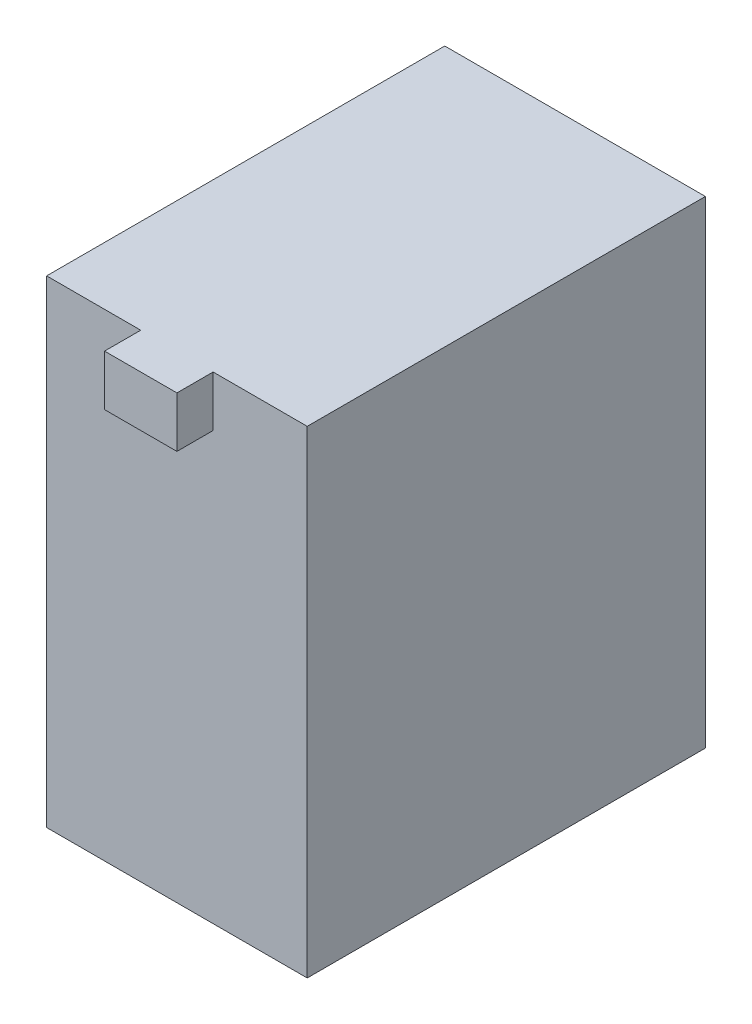
SolidWorks part; units mm, degrees
ref_plane "前视基准面" through (0, 0, 0) normal (0, 0, 1) x (1, 0, 0)
ref_plane "上视基准面" through (0, 0, 0) normal (0, 1, 0) x (1, 0, 0)
ref_plane "右视基准面" through (0, 0, 0) normal (1, 0, 0) x (0, 0, -1)
other "Configuration Table"
sketch "草图1" plane through (0, 0, 0) normal (0, 1, 0) x (1, 0, 0)
  line L1 (-18, -27.5) -> (18, -27.5)
  line L2 (-18, -27.5) -> (-18, 27.5)
  line L3 (-18, 27.5) -> (18, 27.5)
  line L4 (18, -27.5) -> (18, 27.5)
  line L5 (-18, -27.5) -> (18, 27.5) construction
  line L6 (-18, 27.5) -> (18, -27.5) construction
  point P0 (0, 0)
  dimension "D1" = 36
  dimension "D2" = 55
extrude "凸台-拉伸1" add sketch "草图1" along normal blind 66
sketch "草图2" plane through (0, 0, 27.5) normal (0, 0, 1) x (1, 0, 0)
  line L0 (0, 0) -> (0, 68.6632) construction
  line L1 (-5, 66) -> (5, 66)
  line L2 (-18, 66) -> (18, 66) construction
  line L3 (5, 66) -> (5, 59)
  line L4 (5, 59) -> (-5, 59)
  line L5 (-5, 66) -> (-5, 59)
  point P10 (0, 59)
  point P11 (0, 66)
  dimension "D1" = 10
  dimension "D2" = 7
extrude "凸台-拉伸2" add sketch "草图2" along normal blind 5
